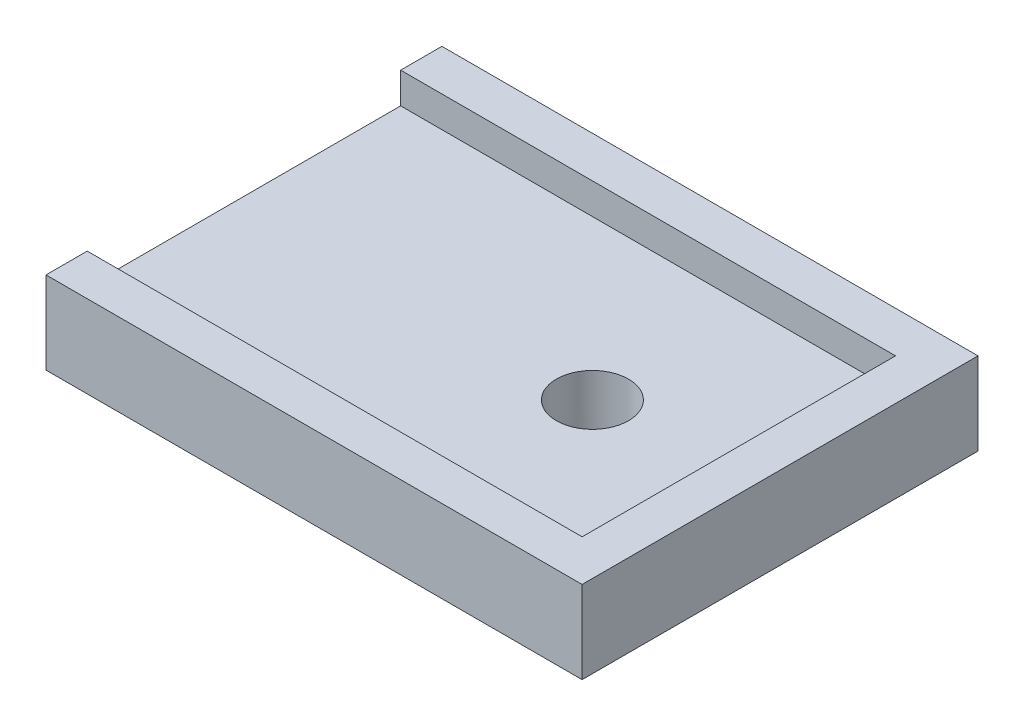
SolidWorks part; units mm, degrees
ref_plane "Front" through (0, 0, 0) normal (0, 0, 1) x (1, 0, 0)
ref_plane "Top" through (0, 0, 0) normal (0, 1, 0) x (1, 0, 0)
ref_plane "Right" through (0, 0, 0) normal (1, 0, 0) x (0, 0, -1)
sketch "Sketch1" plane through (0, 0, 0) normal (0, 1, 0) x (1, 0, 0)
  line L1 (-12, -7.6) -> (12, -7.6)
  line L2 (-12, -7.6) -> (-12, 7.6)
  line L3 (-12, 7.6) -> (12, 7.6)
  line L4 (12, -7.6) -> (12, 7.6)
  line L5 (-12, -7.6) -> (12, 7.6) construction
  line L6 (-12, 7.6) -> (12, -7.6) construction
  point P0 (0, 0)
  dimension "D1" = 24
  dimension "D2" = 15.2
extrude "Boss-Extrude1" add sketch "Sketch1" along normal blind 2.5
sketch "Sketch3" plane through (0, 2.5, 0) normal (0, 1, 0) x (1, 0, 0)
  circle A0 centre (5, -0.1) radius 1.75
  dimension "D1" = 3.5
extrude "Cut-Extrude1" cut sketch "Sketch3" against normal blind 10
sketch "Sketch4" plane through (0, 0, 0) normal (0, -1, 0) x (-1, 0, 0)
  line L6 (12, -9.6) -> (12, -7.6)
  line L7 (12, -7.6) -> (-12, -7.6)
  line L8 (-12, -7.6) -> (-12, 7.6)
  line L9 (-14, 9.6) -> (12, 9.6)
  line L10 (12, -9.6) -> (-14, -9.6)
  line L11 (-14, -9.6) -> (-14, 9.6)
  line L12 (-14, 9.6) -> (12, 9.6)
  line L13 (12, -9.6) -> (-14, -9.6)
  line L14 (-14, -9.6) -> (-14, 9.6)
  line L15 (-12, 7.6) -> (12, 7.6)
  line L16 (12, 7.6) -> (12, 9.6)
  dimension "D1" = 2
extrude "Boss-Extrude2" add sketch "Sketch4" against normal blind 4
